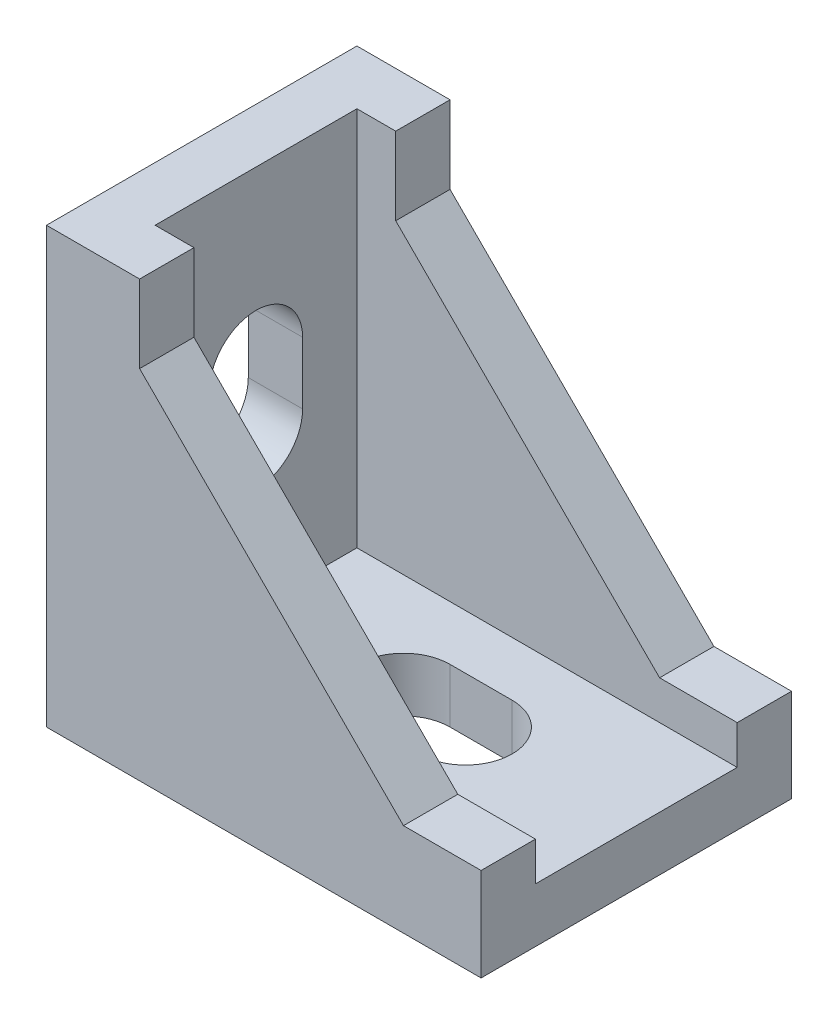
SolidWorks part; units mm, degrees
material "1060 Alloy"
ref_plane "Front Plane" through (0, 0, 0) normal (0, 0, 1) x (1, 0, 0)
ref_plane "Top Plane" through (0, 0, 0) normal (0, 1, 0) x (1, 0, 0)
ref_plane "Right Plane" through (0, 0, 0) normal (1, 0, 0) x (0, 0, -1)
sketch "Sketch1" plane through (0, 0, 0) normal (0, 0, 1) x (1, 0, 0)
  line L0 (0, 28) -> (0, 0)
  line L1 (0, 0) -> (28, 0)
  line L2 (28, 0) -> (28, 3.5)
  line L3 (28, 3.5) -> (3.5, 3.5)
  line L4 (3.5, 3.5) -> (3.5, 28)
  line L5 (3.5, 28) -> (0, 28)
  dimension "D1" = 3.5
  dimension "D2" = 28
  dimension "D3" = 28
extrude "Boss-Extrude1" add sketch "Sketch1" along normal mid plane 20
sketch "Sketch2" plane through (0, 0, 10) normal (0, 0, 1) x (1, 0, 0)
  line L0 (3.5, 28) -> (6, 28)
  line L1 (6, 28) -> (6, 23)
  line L2 (6, 23) -> (23, 6)
  line L3 (23, 6) -> (28, 6)
  line L4 (28, 6) -> (28, 3.5)
  line L5 (28, 3.5) -> (3.5, 3.5)
  line L6 (3.5, 3.5) -> (3.5, 28)
  dimension "D1" = 2.5
  dimension "D2" = 5
extrude "Boss-Extrude2" add sketch "Sketch2" against normal blind 3.5
mirror "Mirror1" about plane through (0, 0, 0) normal (0, 0, 1) of "Boss-Extrude2"
sketch "Sketch3" plane through (0, 3.5, 0) normal (0, 1, 0) x (1, 0, 0)
  line L0 (13, 0) -> (17, 0) construction
  line L1 (13, 3) -> (17, 3)
  line L2 (13, -3) -> (17, -3)
  line L8 (0, -10) -> (0, 10) construction
  arc A0 (13, 3) -> (13, -3) centre (13, 0) ccw
  arc A1 (17, -3) -> (17, 3) centre (17, 0) ccw
  point P3 (15, 0)
  dimension "D1" = 3
  dimension "D2" = 10
  dimension "D3" = 10
extrude "Cut-Extrude1" cut sketch "Sketch3" against normal up to next
sketch "Sketch4" plane through (3.5, 0, 0) normal (1, 0, 0) x (0, 0, -1)
  line L0 (0, 13) -> (0, 17) construction
  line L1 (-3, 13) -> (-3, 17)
  line L2 (3, 13) -> (3, 17)
  arc A0 (-3, 13) -> (3, 13) centre (0, 13) ccw
  arc A1 (3, 17) -> (-3, 17) centre (0, 17) ccw
  point P3 (0, 15)
  dimension "D1" = 3
  dimension "D2" = 10
  dimension "D3" = 10
extrude "Cut-Extrude2" cut sketch "Sketch4" against normal up to next
